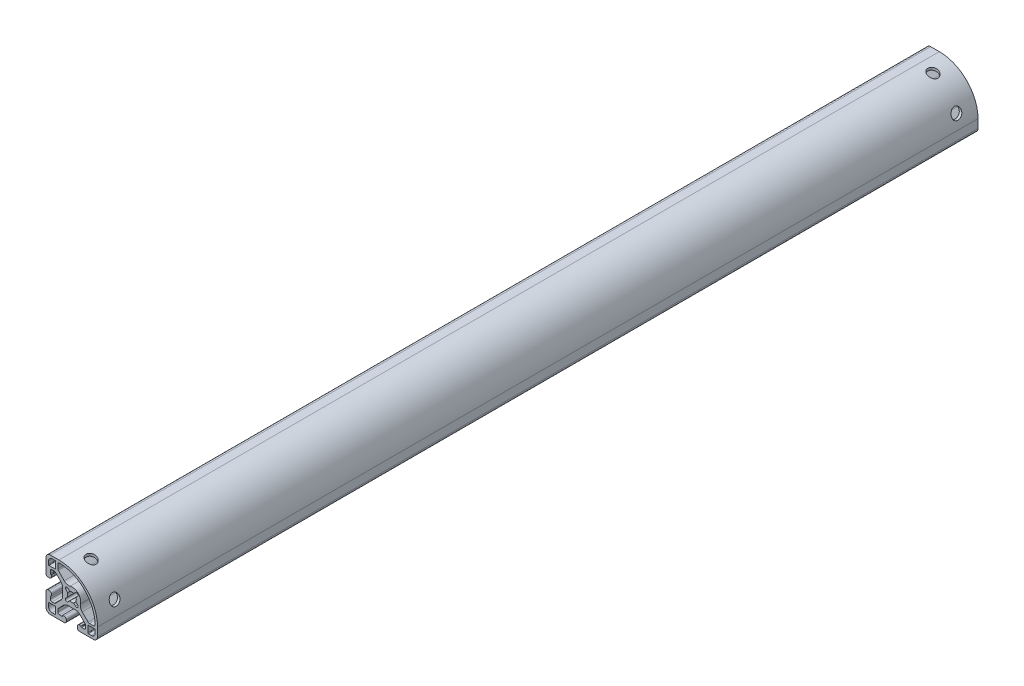
SolidWorks part; units mm, degrees
material "6105-T5 Aluminum"
ref_plane "Front Plane" through (0, 0, 0) normal (0, 0, 1) x (1, 0, 0)
ref_plane "Top Plane" through (0, 0, 0) normal (0, 1, 0) x (1, 0, 0)
ref_plane "Right Plane" through (0, 0, 0) normal (1, 0, 0) x (0, 0, -1)
sketch "Sketch1" plane through (0, 0, 0) normal (0, 0, 1) x (1, 0, 0)
  line L0 (-3.0179, 1.4014) -> (-4.3388, 2.7224)
  line L1 (-2.7224, 4.3388) -> (-1.4014, 3.0179)
  line L2 (1.4014, 3.0179) -> (2.7224, 4.3388)
  line L3 (4.3388, 2.7224) -> (3.0179, 1.4014)
  line L4 (3.0179, -1.4014) -> (4.3388, -2.7224)
  line L5 (2.7224, -4.3388) -> (1.4014, -3.0179)
  line L6 (-1.4014, -3.0179) -> (-2.7224, -4.3388)
  line L7 (-4.3388, -2.7224) -> (-3.0179, -1.4014)
  line L8 (-11.8618, 16.8656) -> (-11.8618, 12.2428)
  line L9 (-12.2428, 11.8618) -> (-16.8656, 11.8618)
  line L10 (-17.2466, 12.2428) -> (-17.2466, 14.4526)
  line L11 (-14.4526, 17.2466) -> (-12.2428, 17.2466)
  line L12 (11.8618, -16.8656) -> (11.8618, -12.2428)
  line L13 (12.2428, -11.8618) -> (16.8656, -11.8618)
  line L14 (17.2466, -12.2428) -> (17.2466, -14.4526)
  line L15 (14.4526, -17.2466) -> (12.2428, -17.2466)
  line L16 (-16.8656, -11.8618) -> (-12.2428, -11.8618)
  line L17 (-11.8618, -12.2428) -> (-11.8618, -16.8656)
  line L18 (-12.2428, -17.2466) -> (-14.4526, -17.2466)
  line L19 (-17.2466, -14.4526) -> (-17.2466, -12.2428)
  line L20 (-5.5668, 7.7221) -> (-9.915, 12.0703)
  line L21 (-10.287, 12.9683) -> (-10.287, 15.9824)
  line L22 (15.9824, -10.287) -> (12.9683, -10.287)
  line L23 (12.0703, -9.915) -> (7.7221, -5.5668)
  line L24 (-7.239, -15.8242) -> (-9.017, -15.8242)
  line L25 (-10.287, -14.5542) -> (-10.287, -12.8105)
  line L26 (-10.0266, -12.1819) -> (-5.9739, -8.1292)
  line L27 (-2.6153, -6.738) -> (2.6153, -6.738)
  line L28 (5.9739, -8.1292) -> (10.0266, -12.1819)
  line L29 (10.287, -12.8105) -> (10.287, -14.5542)
  line L30 (9.017, -15.8242) -> (7.239, -15.8242)
  line L31 (6.858, -15.4432) -> (6.858, -14.986)
  line L32 (6.858, -14.986) -> (5.6388, -14.986)
  line L33 (4.064, -16.5608) -> (4.064, -17.4752)
  line L34 (5.6388, -19.05) -> (15.875, -19.05)
  line L35 (19.05, -15.875) -> (19.05, -9.525)
  line L36 (-9.525, 19.05) -> (-15.875, 19.05)
  line L37 (-19.05, 15.875) -> (-19.05, 5.6388)
  line L38 (-17.4752, 4.064) -> (-16.5608, 4.064)
  line L39 (-14.986, 5.6388) -> (-14.986, 6.858)
  line L40 (-14.986, 6.858) -> (-15.4432, 6.858)
  line L41 (-15.8242, 7.239) -> (-15.8242, 9.017)
  line L42 (-14.5542, 10.287) -> (-12.8105, 10.287)
  line L43 (-12.1819, 10.0266) -> (-8.1292, 5.9739)
  line L44 (-6.738, 2.6153) -> (-6.738, -2.6153)
  line L45 (-8.1292, -5.9739) -> (-12.1819, -10.0266)
  line L46 (-12.8105, -10.287) -> (-14.5542, -10.287)
  line L47 (-15.8242, -9.017) -> (-15.8242, -7.239)
  line L48 (-15.4432, -6.858) -> (-14.986, -6.858)
  line L49 (-14.986, -6.858) -> (-14.986, -5.6388)
  line L50 (-16.5608, -4.064) -> (-17.4752, -4.064)
  line L51 (-19.05, -5.6388) -> (-19.05, -15.875)
  line L52 (-15.875, -19.05) -> (-5.6388, -19.05)
  line L53 (-4.064, -17.4752) -> (-4.064, -16.5608)
  line L54 (-5.6388, -14.986) -> (-6.858, -14.986)
  line L55 (-6.858, -14.986) -> (-6.858, -15.4432)
  arc A0 (-3.0179, 1.4014) -> (-3.0179, -1.4014) centre (0, 0) ccw
  arc A1 (-2.7224, 4.3388) -> (-4.3388, 2.7224) centre (-3.5306, 3.5306) ccw
  arc A2 (1.4014, 3.0179) -> (-1.4014, 3.0179) centre (0, 0) ccw
  arc A3 (4.3388, 2.7224) -> (2.7224, 4.3388) centre (3.5306, 3.5306) ccw
  arc A4 (3.0179, -1.4014) -> (3.0179, 1.4014) centre (0, 0) ccw
  arc A5 (2.7224, -4.3388) -> (4.3388, -2.7224) centre (3.5306, -3.5306) ccw
  arc A6 (-1.4014, -3.0179) -> (1.4014, -3.0179) centre (0, 0) ccw
  arc A7 (-4.3388, -2.7224) -> (-2.7224, -4.3388) centre (-3.5306, -3.5306) ccw
  arc A8 (-12.2428, 11.8618) -> (-11.8618, 12.2428) centre (-12.2428, 12.2428) ccw
  arc A9 (-17.2466, 12.2428) -> (-16.8656, 11.8618) centre (-16.8656, 12.2428) ccw
  arc A10 (-14.4526, 17.2466) -> (-17.2466, 14.4526) centre (-14.4526, 14.4526) ccw
  arc A11 (-11.8618, 16.8656) -> (-12.2428, 17.2466) centre (-12.2428, 16.8656) ccw
  arc A12 (12.2428, -11.8618) -> (11.8618, -12.2428) centre (12.2428, -12.2428) ccw
  arc A13 (17.2466, -12.2428) -> (16.8656, -11.8618) centre (16.8656, -12.2428) ccw
  arc A14 (14.4526, -17.2466) -> (17.2466, -14.4526) centre (14.4526, -14.4526) ccw
  arc A15 (11.8618, -16.8656) -> (12.2428, -17.2466) centre (12.2428, -16.8656) ccw
  arc A16 (-11.8618, -12.2428) -> (-12.2428, -11.8618) centre (-12.2428, -12.2428) ccw
  arc A17 (-12.2428, -17.2466) -> (-11.8618, -16.8656) centre (-12.2428, -16.8656) ccw
  arc A18 (-17.2466, -14.4526) -> (-14.4526, -17.2466) centre (-14.4526, -14.4526) ccw
  arc A19 (-16.8656, -11.8618) -> (-17.2466, -12.2428) centre (-16.8656, -12.2428) ccw
  arc A20 (6.4536, -1.1357) -> (7.7221, -5.5668) centre (11.0807, -2.2082) ccw
  arc A21 (6.4536, -1.1357) -> (-1.1357, 6.4536) centre (0.2923, 0.2923) ccw
  arc A22 (-5.5668, 7.7221) -> (-1.1357, 6.4536) centre (-2.2082, 11.0807) ccw
  arc A23 (-10.287, 12.9683) -> (-9.915, 12.0703) centre (-9.017, 12.9683) ccw
  arc A24 (-8.9917, 17.2521) -> (-10.287, 15.9824) centre (-9.017, 15.9824) ccw
  arc A25 (17.2521, -8.9917) -> (-8.9917, 17.2521) centre (-9.525, -9.525) ccw
  arc A26 (15.9824, -10.287) -> (17.2521, -8.9917) centre (15.9824, -9.017) ccw
  arc A27 (12.0703, -9.915) -> (12.9683, -10.287) centre (12.9683, -9.017) ccw
  arc A28 (-7.239, -15.8242) -> (-6.858, -15.4432) centre (-7.239, -15.4432) ccw
  arc A29 (-10.287, -14.5542) -> (-9.017, -15.8242) centre (-9.017, -14.5542) ccw
  arc A30 (-10.0266, -12.1819) -> (-10.287, -12.8105) centre (-9.398, -12.8105) ccw
  arc A31 (-2.6153, -6.738) -> (-5.9739, -8.1292) centre (-2.6153, -11.4878) ccw
  arc A32 (5.9739, -8.1292) -> (2.6153, -6.738) centre (2.6153, -11.4878) ccw
  arc A33 (10.287, -12.8105) -> (10.0266, -12.1819) centre (9.398, -12.8105) ccw
  arc A34 (9.017, -15.8242) -> (10.287, -14.5542) centre (9.017, -14.5542) ccw
  arc A35 (6.858, -15.4432) -> (7.239, -15.8242) centre (7.239, -15.4432) ccw
  arc A36 (5.6388, -14.986) -> (4.064, -16.5608) centre (5.6388, -16.5608) ccw
  arc A37 (4.064, -17.4752) -> (5.6388, -19.05) centre (5.6388, -17.4752) ccw
  arc A38 (15.875, -19.05) -> (19.05, -15.875) centre (15.875, -15.875) ccw
  arc A39 (19.05, -9.525) -> (-9.525, 19.05) centre (-9.525, -9.525) ccw
  arc A40 (-15.875, 19.05) -> (-19.05, 15.875) centre (-15.875, 15.875) ccw
  arc A41 (-19.05, 5.6388) -> (-17.4752, 4.064) centre (-17.4752, 5.6388) ccw
  arc A42 (-16.5608, 4.064) -> (-14.986, 5.6388) centre (-16.5608, 5.6388) ccw
  arc A43 (-15.8242, 7.239) -> (-15.4432, 6.858) centre (-15.4432, 7.239) ccw
  arc A44 (-14.5542, 10.287) -> (-15.8242, 9.017) centre (-14.5542, 9.017) ccw
  arc A45 (-12.1819, 10.0266) -> (-12.8105, 10.287) centre (-12.8105, 9.398) ccw
  arc A46 (-6.738, 2.6153) -> (-8.1292, 5.9739) centre (-11.4878, 2.6153) ccw
  arc A47 (-8.1292, -5.9739) -> (-6.738, -2.6153) centre (-11.4878, -2.6153) ccw
  arc A48 (-12.8105, -10.287) -> (-12.1819, -10.0266) centre (-12.8105, -9.398) ccw
  arc A49 (-15.8242, -9.017) -> (-14.5542, -10.287) centre (-14.5542, -9.017) ccw
  arc A50 (-15.4432, -6.858) -> (-15.8242, -7.239) centre (-15.4432, -7.239) ccw
  arc A51 (-14.986, -5.6388) -> (-16.5608, -4.064) centre (-16.5608, -5.6388) ccw
  arc A52 (-17.4752, -4.064) -> (-19.05, -5.6388) centre (-17.4752, -5.6388) ccw
  arc A53 (-19.05, -15.875) -> (-15.875, -19.05) centre (-15.875, -15.875) ccw
  arc A54 (-5.6388, -19.05) -> (-4.064, -17.4752) centre (-5.6388, -17.4752) ccw
  arc A55 (-4.064, -16.5608) -> (-5.6388, -14.986) centre (-5.6388, -16.5608) ccw
extrude "Extrude1" add sketch "Sketch1" against normal blind 650.8496
sketch "Sketch2" plane through (0, -19.05, 0) normal (0, -1, 0) x (1, 0, 0)
  line L0 (5.6388, 0) -> (15.875, 0) construction
  circle A0 centre (0, -14.2748) radius 3.7465
  dimension "D1" = 7.493
  dimension "D2" = 14.2748
extrude "7050-R-LEFT-OPEN" cut sketch "Sketch2" against normal through all
sketch "Sketch3" plane through (-19.05, 0, 0) normal (-1, 0, 0) x (0, 0, 1)
  line L0 (0, -5.6388) -> (0, -15.875) construction
  circle A0 centre (-14.2748, 0) radius 3.7465
  dimension "D1" = 7.493
  dimension "D2" = 14.2748
extrude "7050-S-LEFT-OPEN" cut sketch "Sketch3" against normal through all
sketch "Sketch5" plane through (0, -19.05, 0) normal (0, -1, 0) x (1, 0, 0)
  line L0 (5.6388, -650.8496) -> (15.875, -650.8496) construction
  circle A0 centre (0, -636.5748) radius 3.7465
  dimension "D1" = 7.493
  dimension "D2" = 14.2748
extrude "7050-R-LEFT-OPEN-2" cut sketch "Sketch5" against normal through all
sketch "Sketch4" plane through (-19.05, 0, 0) normal (-1, 0, 0) x (0, 0, 1)
  line L0 (-650.8496, -5.6388) -> (-650.8496, -15.875) construction
  circle A0 centre (-636.5748, 0) radius 3.7465
  dimension "D1" = 7.493
  dimension "D2" = 14.2748
extrude "7050-S-LEFT-OPEN-2" cut sketch "Sketch4" against normal through all
